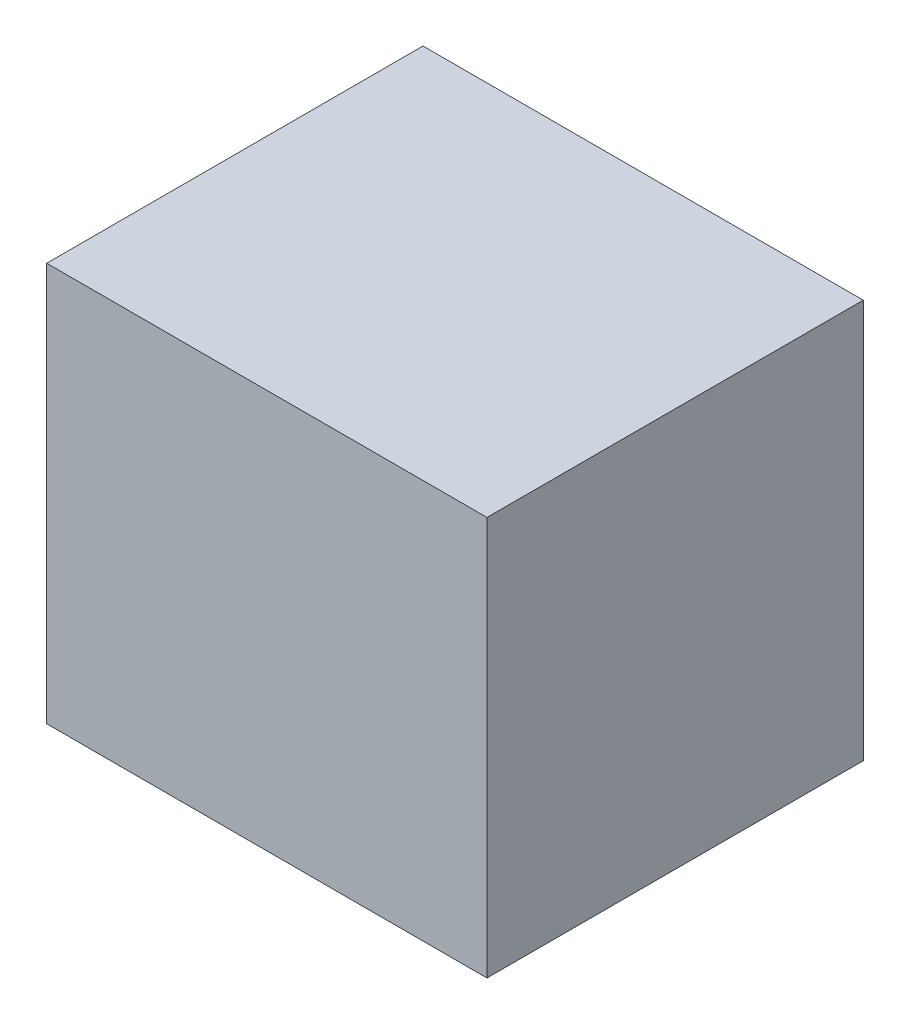
SolidWorks part; units mm, degrees
ref_plane "Front Plane" through (0, 0, 0) normal (0, 0, 1) x (1, 0, 0)
ref_plane "Top Plane" through (0, 0, 0) normal (0, 1, 0) x (1, 0, 0)
ref_plane "Right Plane" through (0, 0, 0) normal (1, 0, 0) x (0, 0, -1)
sketch "Sketch1" plane through (0, 0, 0) normal (0, 0, 1) x (1, 0, 0)
  line L0 (-1.5283, -1.2446) -> (1.4435, -1.2446)
  line L1 (1.4435, -1.2446) -> (1.4435, 1.4478)
  line L2 (1.4435, 1.4478) -> (-1.5283, 1.4478)
  line L3 (-1.5283, 1.4478) -> (-1.5283, -1.2446)
extrude "Component_Outline" add sketch "Sketch1" along normal blind 2.54 separate body
sketch3d "3DSketch1"
  line L0 (0, 0, 0) -> (1, 0, 0)
  line L1 (0, 0, 0) -> (0, 1, 0)
  line L2 (0, 0, 0) -> (0, 0, 1)
  point P0 (0, 0, 0)
